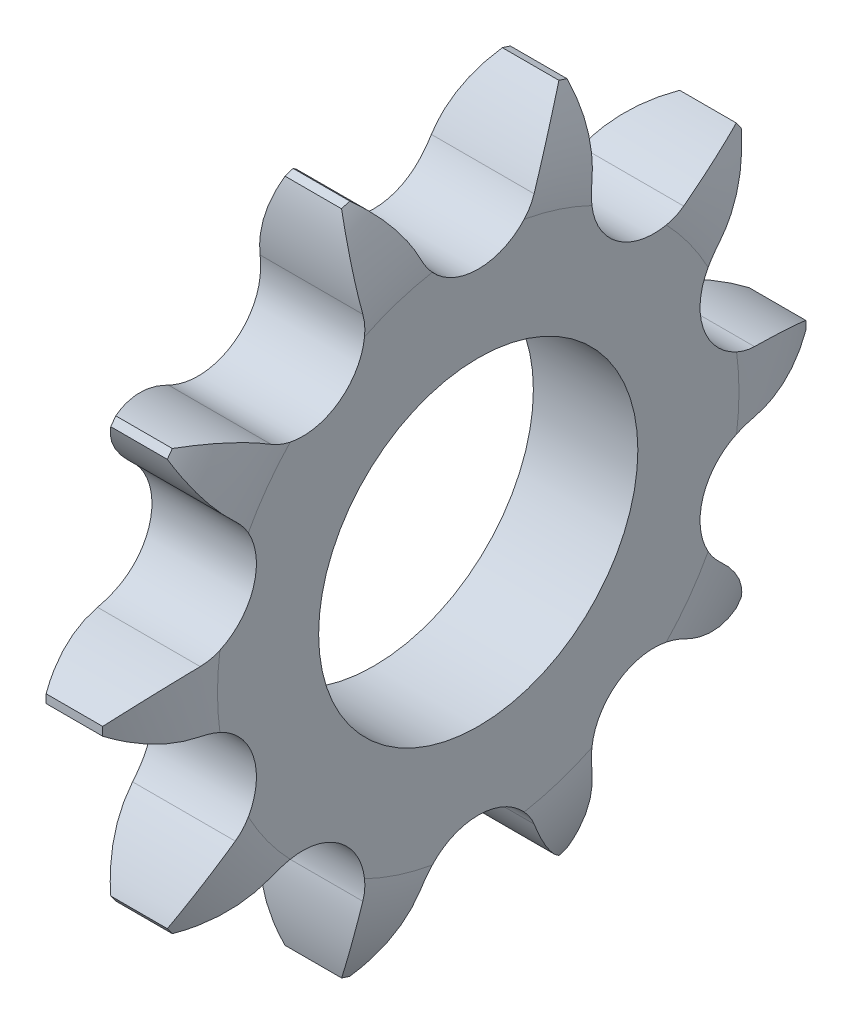
SolidWorks part; units mm, degrees
ref_plane "Plane1" through (0, 0, 0) normal (0, 0, 1) x (1, 0, 0)
ref_plane "Plane2" through (0, 0, 0) normal (0, 1, 0) x (1, 0, 0)
ref_plane "Plane3" through (0, 0, 0) normal (1, 0, 0) x (0, 0, -1)
sketch "Clipboard" plane through (0, 0, 0) normal (0, 1, 0) x (1, 0, 0)
  line L0 (0, 0) -> (12.5071, -2.2053)
  line L1 (-15, 0) -> (100, 0) construction
  line L2 (0, 0) -> (-1.094, 1.2365)
  line L3 (0, 0) -> (-11.863, 4.5341)
  line L4 (0, 0) -> (3.0529, 0.5383)
  line L5 (0, 0) -> (-46.8476, -17.4728)
  line L6 (0, 0) -> (-5.9685, -4.027)
  line L7 (-1.094, 1.2365) -> (47.9878, 10.777)
  line L8 (-76.2, 38.1) -> (-72.9, 38.1)
  line L9 (-73.4259, 41.6592) -> (-72.8306, 41.7344)
  line L10 (-73.7265, 13.0465) -> (-59.8065, 13.0465)
  circle A0 centre (0, 0) radius 4.255
  circle A1 centre (0, 0) radius 13.0221
  circle A2 centre (0, 0) radius 37.5
  dimension "Dr" = 8.51
  dimension "MHD" = 26.0442
  dimension "Hub_dia" = 75
  dimension "Num_teeth" = 10
  dimension "Pitch" = 12.7
  dimension "Width" = 3.1
  dimension "Side_relief" = 1.651
  dimension "Side_radius" = 12.7
  dimension "Overall_len" = 50
  dimension "Show_teeth" = 10
  dimension "Thickness" = 7.2
  dimension "OAL" = 50.0005
  dimension "T_dim" = 3.3
  dimension "Fillet_rad" = 0.6
  dimension "Face_width" = 7.2
  dimension "Num_strands" = 1
  dimension "Transv_pitch" = 13.92
  dimension "Plate_wid" = 11.81
sketch "BasProSke" plane through (0, 0, 0) normal (0, 1, 0) x (1, 0, 0)
  line L0 (-10, 0) -> (60, 0) construction
  line L1 (0, 0) -> (0, 17.9698)
  line L2 (0, 0) -> (7.2, 0)
  line L3 (7.2, 0) -> (7.2, 17.9698)
  line L4 (5.549, 24.2315) -> (1.651, 24.2315)
  arc A0 (0, 17.9698) -> (1.651, 24.2315) centre (12.7, 17.9698) cw
  arc A1 (7.2, 17.9698) -> (5.549, 24.2315) centre (-5.5, 17.9698) ccw
  dimension "Thickness" = 7.2
  dimension "D1" = 12.7
  dimension "G1" = 1.651
  dimension "G2" = 1.651
  dimension "Diameter" = 48.4631
revolve "Base-Revolve" add sketch "BasProSke" angle 360 about L0
sketch "TooCutSke" plane through (0, 0, 0) normal (1, 0, 0) x (0, 0, -1)
  line L0 (0, 20.5916) -> (3.9106, 18.8094) construction
  line L1 (0, 0) -> (0, 107) construction
  line L2 (0, 20.5916) -> (-10, 20.5916) construction
  line L3 (0, 20.5916) -> (-3.9106, 18.8094) construction
  arc A0 (3.9106, 18.8094) -> (7.6796, 23.509) centre (15.0616, 13.7276) cw
  arc A1 (3.9106, 18.8094) -> (-3.9106, 18.8094) centre (0, 20.5916) cw
  arc A2 (-3.9106, 18.8094) -> (-7.6796, 23.509) centre (-15.0616, 13.7276) ccw
  arc A3 (7.6796, 23.509) -> (-7.6796, 23.509) centre (0, 0) ccw
  dimension "R1" = 4.2976
  dimension "R2" = 12.2544
  dimension "Overcut" = 24.7315
  dimension "Seat_radius" = 20.5916
  dimension "X" = 131
extrude "ToothCut" cut sketch "TooCutSke" along normal through all
pattern_circular "TeethCuts" count 10 every 36 about axis through (-10, 0, 0) along (1, 0, 0) of "ToothCut"
sketch "HubNeaOneSke" plane through (0, 0, 0) normal (-1, 0, 0) x (0, 0, 1)
  circle A0 centre (0, 0) radius 13.0221
  dimension "Diameter" = 26.0442
extrude "HubNearOne" [suppressed] add sketch "HubNeaOneSke" along normal blind 42.8005
fillet "HubNearOneFillet" [suppressed] radius 0.6
sketch "HubNeaBotSke" plane through (0, 0, 0) normal (-1, 0, 0) x (0, 0, 1)
  circle A0 centre (0, 0) radius 13.0221
  dimension "Diameter" = 26.0442
extrude "HubNearBoth" [suppressed] add sketch "HubNeaBotSke" along normal blind 21.4002
fillet "HubNearBothFillet" [suppressed] radius 0.6
ref_plane "FarPln" through (7.2, 0, 0) normal (1, 0, 0) x (0, 0, -1)
sketch "HubFarSke" plane through (7.2, 0, 0) normal (1, 0, 0) x (0, 0, -1)
  circle A0 centre (0, 0) radius 13.0221
  dimension "Diameter" = 26.0442
extrude "HubFar" [suppressed] add sketch "HubFarSke" along normal blind 21.4002
fillet "HubFarFillet" [suppressed] radius 0.6
sketch "BorSke" plane through (0, 0, 0) normal (1, 0, 0) x (0, 0, -1)
  circle A0 centre (0, 0) radius 11
  dimension "Diameter" = 22
extrude "Bore" cut sketch "BorSke" along normal mid plane 100.001
sketch "KeySke" plane through (0, 0, 0) normal (1, 0, 0) x (0, 0, -1)
  line L0 (-3, 0) -> (-3, 14.3)
  line L1 (-3, 14.3) -> (3, 14.3)
  line L2 (3, 14.3) -> (3, 0)
  line L3 (0, 0) -> (0, 34) construction
  line L4 (-3, 0) -> (3, 0)
  dimension "Offset" = 14.3
  dimension "Width" = 6
extrude "Keyway" [suppressed] cut sketch "KeySke" along normal mid plane 100.001
pattern_circular "Keyway2" [suppressed] count 2 every 90 about axis through (-10, 0, 0) along (1, 0, 0)
equation "' \"Pitch@Clipboard\" = 12.7"
equation "' \"Num_strands@Clipboard\" = 1"
equation "' \"Num_teeth@Clipboard\" = 9"
equation "' \"Hub_dia@Clipboard\" = 50"
equation "' \"Overall_len@Clipboard\" = 3"
equation "' \"Diameter@BorSke\" = 12"
equation "' \"T_dim@Clipboard\" = 1"
equation "' \"Width@KeySke\" = 2"
equation "' \"Dr@Clipboard\" = 8.51"
equation "' \"Face_width@Clipboard\" = 7.2"
equation "' \"Side_radius@Clipboard\" = 12.7"
equation "' \"Side_relief@Clipboard\" = 1.27"
equation "' \"Transv_pitch@Clipboard\" = 13.92"
equation "' \"Show_teeth@Clipboard\" = 9"
equation "' \"Fillet_rad@Clipboard\" = 0.6"
equation "' \"Plate_wid@Clipboard\" = 11.8"
equation "\"Num_teeth@Clipboard\" = int( \"Num_teeth@Clipboard\" )"
equation "\"Num_teeth@Clipboard\" = ((sgn( \"Num_teeth@Clipboard\" - 5.0)+1)*( \"Num_teeth@Clipboard\" - 5.0))/2 +5.0"
equation "\"Num_teeth@Clipboard\" = ((sgn( \"Num_teeth@Clipboard\" - 200.0)-1)*( \"Num_teeth@Clipboard\" - 200.0))/-2 +200.0"
equation "\"MHD@Clipboard\" = \"Pitch@Clipboard\" * (1.0 / tan(3.14159265 / \"Num_teeth@Clipboard\" )) - 1.04 * \"Plate_wid@Clipboard\" - 0.76"
equation "\"Thickness@Clipboard\"  = \"Face_width@Clipboard\" + (\"Num_strands@Clipboard\" - 1) * \"Transv_pitch@Clipboard\""
equation "\"OAL@Clipboard\" = \"Thickness@Clipboard\" + 2 * \"Fillet_rad@Clipboard\" + 1"
equation "\"MHD@Clipboard\" = ((sgn( \"MHD@Clipboard\" - \"Hub_dia@Clipboard\" )-1)*( \"MHD@Clipboard\" - \"Hub_dia@Clipboard\" ))/-2+ \"Hub_dia@Clipboard\""
equation "\"OAL@Clipboard\" = ((sgn( \"OAL@Clipboard\" - \"Overall_len@Clipboard\" )+1)*( \"OAL@Clipboard\" - \"Overall_len@Clipboard\" ))/2 + \"Overall_len@Clipboard\" + 0.0005"
equation "\"Num_teeth@TeethCuts\" = int( \"Show_teeth@Clipboard\" ) + 1"
equation "\"Num_teeth@TeethCuts\" = ((sgn( \"Num_teeth@TeethCuts\" - \"Num_teeth@Clipboard\" )-1)*( \"Num_teeth@TeethCuts\" - \"Num_teeth@Clipboard\" ))/-2+ \"Num_teeth@Clipboard\""
equation "\"Num_teeth@TeethCuts\" = ((sgn( \"Num_teeth@TeethCuts\" - 2.0)+1)*( \"Num_teeth@TeethCuts\" - 2.0))/2 +2.0"
equation "\"Angle@TeethCuts\" = 360.0 / \"Num_teeth@Clipboard\""
equation "\"Seat_radius@TooCutSke\" = ( \"Pitch@Clipboard\" / 2.0) / sin(3.14159265 / \"Num_teeth@Clipboard\" ) - \"Dr@Clipboard\" / 2.0 + \"Dr@Clipboard\" * 0.505"
equation "\"R1@TooCutSke\"  = \"Dr@Clipboard\" * 0.505"
equation "\"X@TooCutSke\" = 140.0 - (90.0 / \"Num_teeth@Clipboard\")"
equation "\"R2@TooCutSke\" = 0.12 * \"Dr@Clipboard\" * ( \"Num_teeth@Clipboard\" + 2.0)"
equation "\"Overcut@TooCutSke\" = 0.5 + 0.625 * \"Pitch@Clipboard\" - 0.5 * \"Dr@Clipboard\"  +  \"Pitch@Clipboard\" / 2.0 / sin(3.14159265 / \"Num_teeth@Clipboard\" )"
equation "\"Diameter@BasProSke\" = 2.0 * ( 0.625 * \"Pitch@Clipboard\" - 0.5 * \"Dr@Clipboard\"  +  \"Pitch@Clipboard\" / 2.0 / sin(3.14159265 / \"Num_teeth@Clipboard\" ))"
equation "\"Thickness@BasProSke\"  = \"Thickness@Clipboard\""
equation "\"G1@BasProSke\" =  \"Side_relief@Clipboard\""
equation "\"G2@BasProSke\" =  \"Side_relief@Clipboard\""
equation "\"D1@BasProSke\" =  \"Side_radius@Clipboard\""
equation "\"Diameter@HubNeaOneSke\" = \"MHD@Clipboard\""
equation "\"Length@HubNearOne\" = \"OAL@Clipboard\" - \"Thickness@BasProSke\""
equation "\"Diameter@HubNeaBotSke\" = \"MHD@Clipboard\""
equation "\"Length@HubNearBoth\" = ( \"OAL@Clipboard\" - \"Thickness@BasProSke\" ) / 2.0"
equation "\"D1@HubNearOneFillet\" = \"Fillet_rad@Clipboard\""
equation "\"D1@HubNearBothFillet\" = \"Fillet_rad@Clipboard\""
equation "\"Thickness@FarPln\" = \"Thickness@BasProSke\""
equation "\"Diameter@HubFarSke\" = \"MHD@Clipboard\""
equation "\"Length@HubFar\" = ( \"OAL@Clipboard\" - \"Thickness@BasProSke\" ) / 2.0"
equation "\"D1@HubFarFillet\" = \"Fillet_rad@Clipboard\""
equation "\"D1@Bore\" = \"OAL@Clipboard\" * 2.0"
equation "\"D1@Keyway\" = \"OAL@Clipboard\" * 2.0"
equation "\"Offset@KeySke\" = \"T_dim@Clipboard\" + \"Diameter@BorSke\" / 2.0"
